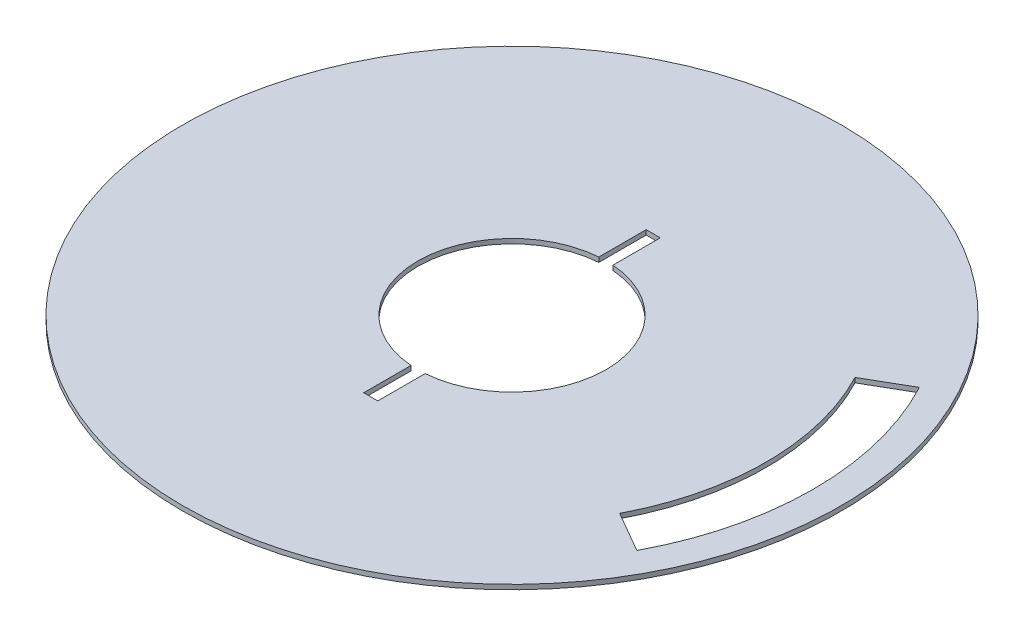
SolidWorks part; units mm, degrees
ref_plane "Ön Düzlem" through (0, 0, 0) normal (0, 0, 1) x (1, 0, 0)
ref_plane "Üst Düzlem" through (0, 0, 0) normal (0, 1, 0) x (1, 0, 0)
ref_plane "Sağ Düzlem" through (0, 0, 0) normal (1, 0, 0) x (0, 0, -1)
sketch "Çizim1" plane through (0, 0, 0) normal (0, 1, 0) x (1, 0, 0)
  line L0 (7.5, -150) -> (7.5, -99.7184)
  line L1 (7.5, -150) -> (-7.5, -150)
  line L2 (-7.5, -150) -> (-7.5, -99.7184)
  line L3 (7.5, 150) -> (7.5, 99.7184)
  line L4 (-7.5, 150) -> (-7.5, 99.7184)
  line L5 (-7.5, 150) -> (7.5, 150)
  line L6 (-30, -165.3939) -> (-30, -95.3939)
  line L7 (-30, -95.3939) -> (-100, -95.3939)
  line L8 (-100, -95.3939) -> (-100, 95.3939)
  line L9 (-100, 95.3939) -> (-30, 95.3939)
  line L10 (30, 95.3939) -> (100, 95.3939)
  line L11 (100, 95.3939) -> (100, -95.3939)
  line L12 (30, -95.3939) -> (30, -165.3939)
  line L13 (30, -95.3939) -> (100, -95.3939)
  line L14 (-30, 95.3939) -> (-30, 165.3939)
  line L15 (30, 165.3939) -> (30, 95.3939)
  line L16 (239.322, 125) -> (282.6559, 150.0188)
  line L17 (239.322, -125) -> (282.6559, -150.0188)
  line L18 (-30, 0) -> (44.5354, 0) construction
  circle A0 centre (0, 0) radius 350
  arc A1 (7.5, -99.7184) -> (7.5, 99.7184) centre (0, 0) ccw
  arc A2 (-7.5, 99.7184) -> (-7.5, -99.7184) centre (0, 0) ccw
  arc A3 (282.6559, 150.0188) -> (282.6559, -150.0188) centre (0, 0) cw
  arc A4 (239.322, 125) -> (239.322, -125) centre (0, 0) cw
  point P14 (0, 0)
  point P30 (0, 0)
  point P31 (313.3441, 64.9267)
  point P32 (0, 0)
  point P33 (0, 0)
  dimension "D1" = 700
  dimension "D2" = 200
  dimension "D9" = 320
  dimension "D10" = 50
  dimension "D3" = 150
  dimension "D4" = 15
  dimension "D6" = 60
  dimension "D7" = 70
  dimension "D8" = 70
  dimension "D11" = 30
  dimension "D12" = 30
  dimension "D13" = 250
  dimension "D14" = 125
  dimension "D5" = 2
extrude "Yükseklik-Ekstrüzyon2" add sketch "Çizim1" along normal blind 5
